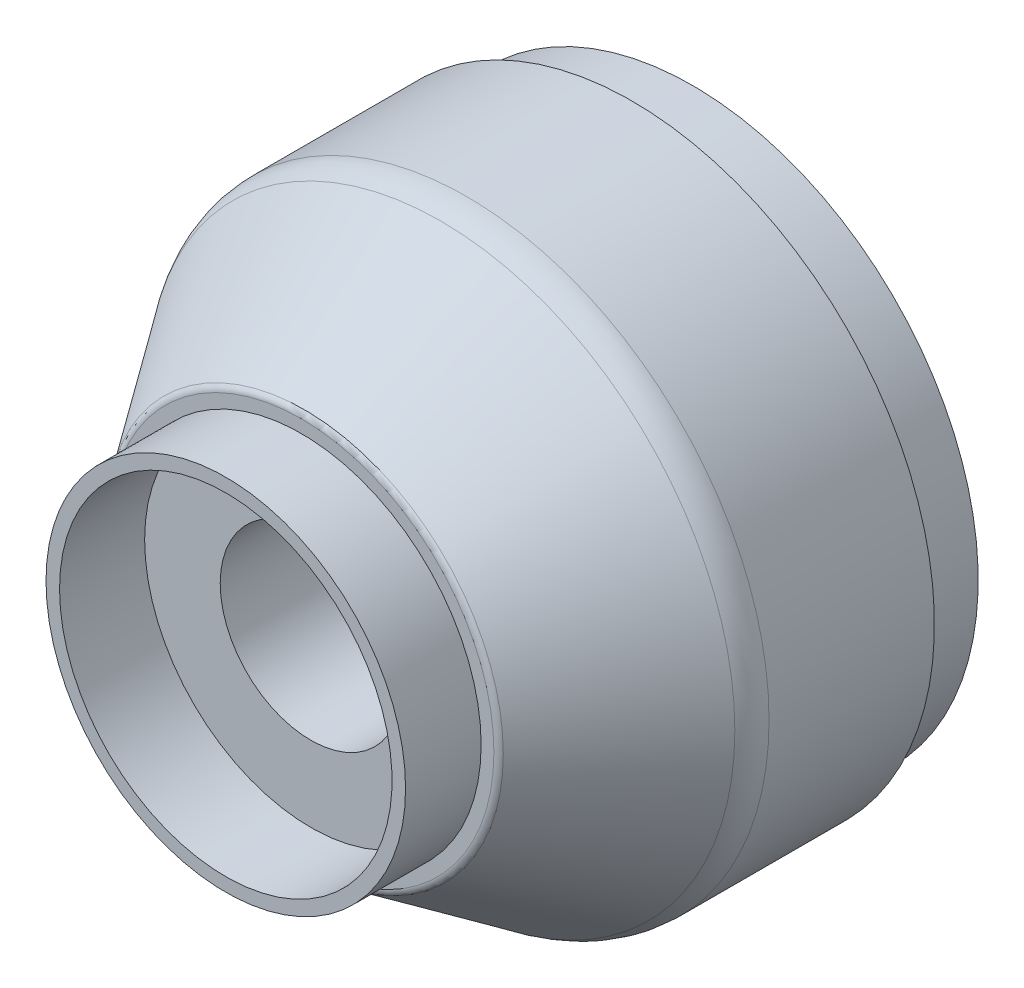
SolidWorks part; units mm, degrees
material "6061 Alloy"
ref_plane "Front Plane" through (0, 0, 0) normal (0, 0, 1) x (1, 0, 0)
ref_plane "Top Plane" through (0, 0, 0) normal (0, 1, 0) x (1, 0, 0)
ref_plane "Right Plane" through (0, 0, 0) normal (1, 0, 0) x (0, 0, -1)
sketch "base-sketch-1" plane through (0, 0, 0) normal (0, 0, 1) x (1, 0, 0)
  circle A0 centre (0, 0) radius 17.5 construction
  dimension "D1" = 35
sketch "base-sketch-2" plane through (0, 0, 0) normal (0, 1, 0) x (1, 0, 0)
  line L0 (0, 0) -> (0, -16) construction
  line L1 (18, -0.7419) -> (18, -16)
  line L2 (18, -16) -> (11, -26)
  line L3 (0, -16) -> (18, -16) construction
  line L4 (11, -26) -> (11, -31.6304)
  line L5 (20, -0.7419) -> (20, -16.6304)
  line L6 (20, -16.6304) -> (13, -26.6304)
  line L7 (13, -26.6304) -> (13, -31.6304)
  line L8 (18, -0.7419) -> (20, -0.7419)
  line L9 (11, -31.6304) -> (13, -31.6304)
  line L10 (13, -26.6304) -> (12, -26.6304) construction
  line L12 (20, -4.7419) -> (19, -4.7419) construction
  line L13 (12, -26.6304) -> (12, -31.6304) construction
  line L14 (11, -26) -> (6, -26)
  line L15 (6, -26) -> (6, -18)
  line L16 (6, -18) -> (16.6, -18)
  line L17 (19, -4.7419) -> (19, -0.7419) construction
  line L18 (20, -4.7419) -> (18.8956, -4.7419)
  line L19 (18.8956, -4.7419) -> (18.8956, -0.7419)
  line L20 (13, -26.6304) -> (11.8956, -26.6304)
  line L21 (11.8956, -26.6304) -> (11.8956, -31.6304)
  line L22 (16.25, -18) -> (16.25, -16)
  line L23 (16.25, -16) -> (18, -3.95)
  line L24 (18, -3.95) -> (0, -3.95) construction
  line L27 (-16.0588, -3.95) -> (17.3848, -3.95) construction
  line L29 (-17.5, -0.7419) -> (17.5, -0.7419) construction
  dimension "D1" = 16
  dimension "D3" = 18
  dimension "D4" = 6
  dimension "D7" = 11
  dimension "D6" = 0.1044
  dimension "D5" = 0.1044
  dimension "D8" = 4
  dimension "D10" = 5
  dimension "D11" = 5
  dimension "D12" = 2
  dimension "D13" = 10
  dimension "D14" = 1.75
  dimension "D9" = 0
  dimension "D2" = 2
revolve "Revolve1" add sketch "base-sketch-2" angle 360 about L0
fillet "Fillet1" radius 3 1 edges at (-20, 0, 16.6304)
fillet "Fillet2" radius 0.5 1 edges at (-13, 0, 26.6304)
equation "\"Tolerance\"=0.208791"
equation "\"D6@base-sketch-2\"=\"Tolerance\"/2"
equation "\"D5@base-sketch-2\"=\"Tolerance\"/2"
